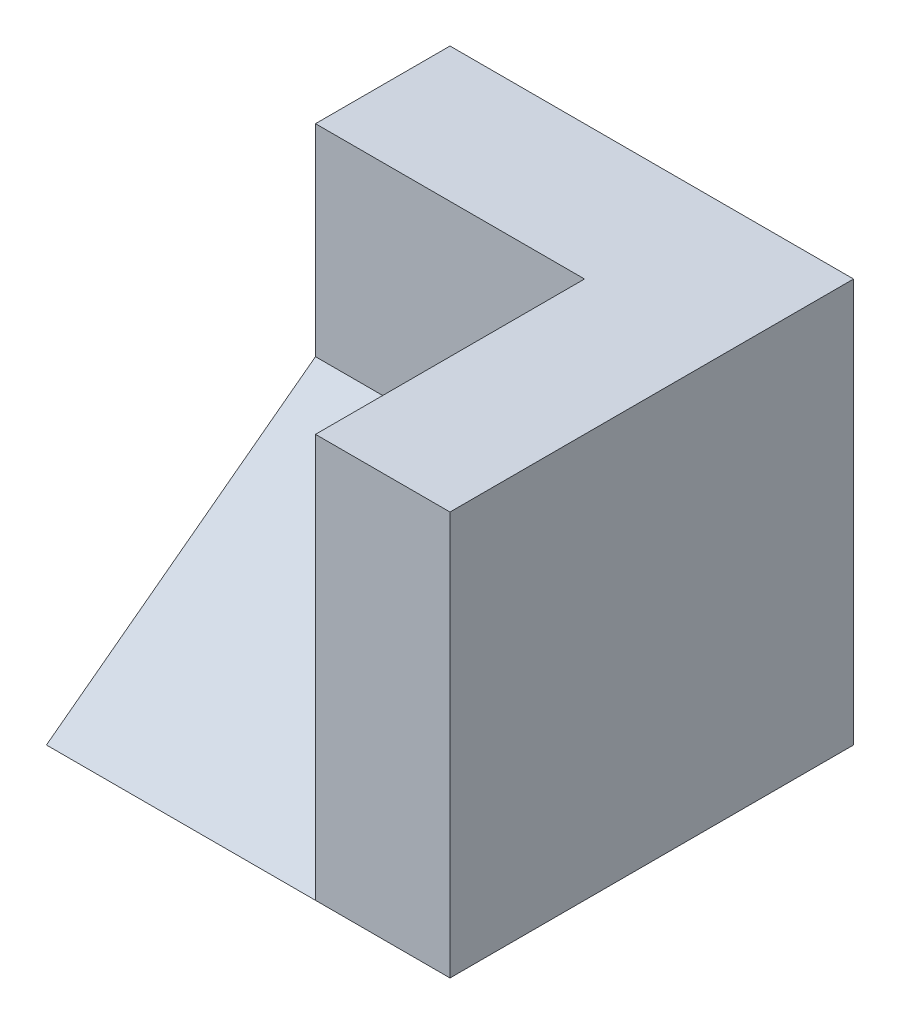
SolidWorks part; units mm, degrees
ref_plane "Alzado" through (0, 0, 0) normal (0, 0, 1) x (1, 0, 0)
ref_plane "Planta" through (0, 0, 0) normal (0, 1, 0) x (1, 0, 0)
ref_plane "Vista lateral" through (0, 0, 0) normal (1, 0, 0) x (0, 0, -1)
sketch "Croquis1" plane through (0, 0, 0) normal (0, 0, 1) x (1, 0, 0)
  line L0 (0, 0) -> (60, 0)
  line L1 (60, 0) -> (60, 60)
  line L2 (60, 60) -> (0, 60)
  line L3 (0, 60) -> (0, 0)
  dimension "D1" = 60
  dimension "D2" = 60
extrude "Saliente-Extruir1" add sketch "Croquis1" against normal blind 60
sketch "Croquis2" plane through (0, 60, 0) normal (0, 1, 0) x (1, 0, 0)
  line L0 (0, 0) -> (0, 40)
  line L1 (0, 60) -> (0, 0) construction
  line L2 (0, 40) -> (40, 40)
  line L3 (40, 40) -> (40, 0)
  line L4 (60, 0) -> (0, 0) construction
  line L5 (40, 0) -> (0, 0)
  line L6 (60, 60) -> (60, 0) construction
  dimension "D1" = 20
  dimension "D2" = 40
extrude "Cortar-Extruir1" cut sketch "Croquis2" against normal blind 60
sketch "Croquis3" plane through (40, 0, 0) normal (-1, 0, 0) x (0, 0, 1)
  line L0 (-40, 30) -> (0, 0)
  line L1 (-40, 0) -> (-40, 60) construction
  line L2 (0, 0) -> (-40, 0)
  line L3 (-40, 0) -> (-40, 30)
extrude "Saliente-Extruir2" add sketch "Croquis3" along normal blind 40
